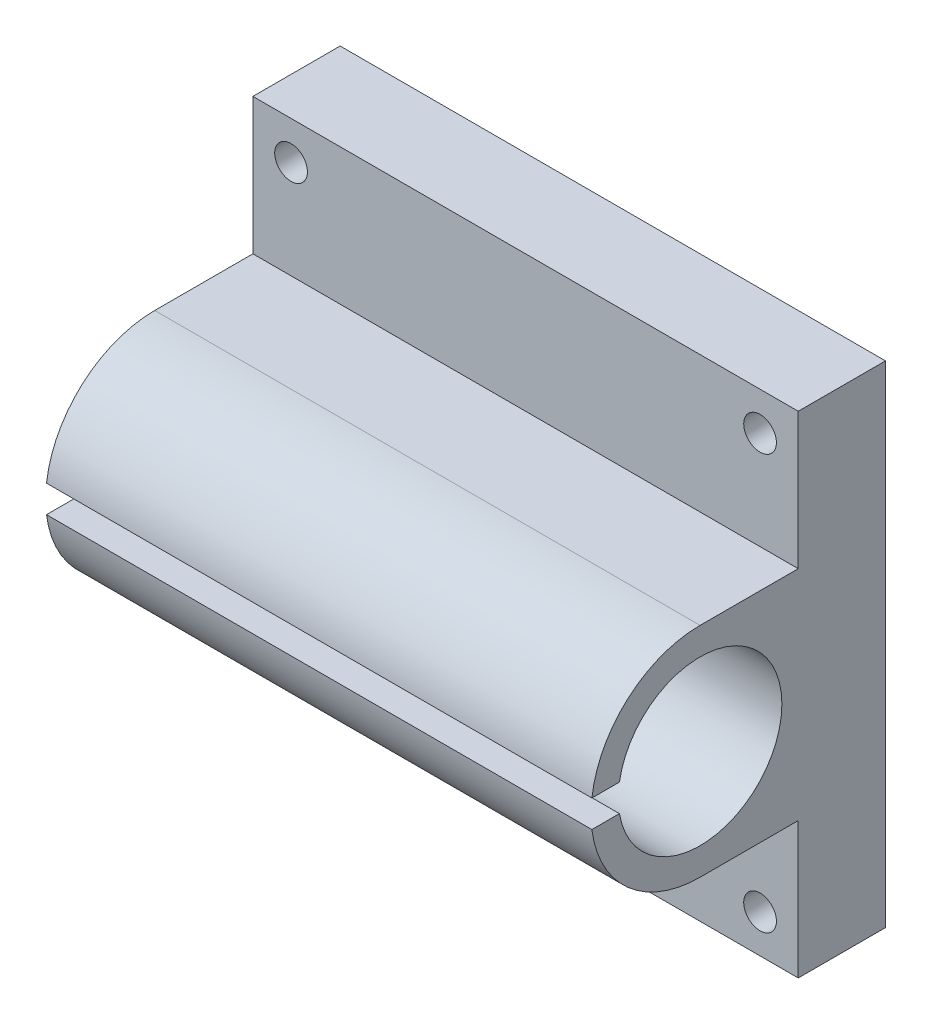
SolidWorks part; units mm, degrees
ref_plane "前视基准面" through (0, 0, 0) normal (0, 0, 1) x (1, 0, 0)
ref_plane "上视基准面" through (0, 0, 0) normal (0, 1, 0) x (1, 0, 0)
ref_plane "右视基准面" through (0, 0, 0) normal (1, 0, 0) x (0, 0, -1)
sketch "草图1" plane through (0, 0, 0) normal (0, 0, 1) x (1, 0, 0)
  line L1 (-25, -22.5) -> (25, -22.5)
  line L2 (-25, -22.5) -> (-25, 22.5)
  line L3 (-25, 22.5) -> (25, 22.5)
  line L4 (25, -22.5) -> (25, 22.5)
  line L5 (-25, -22.5) -> (25, 22.5) construction
  line L6 (-25, 22.5) -> (25, -22.5) construction
  point P0 (0, 0)
  dimension "D1" = 45
  dimension "D2" = 50
extrude "凸台-拉伸1" add sketch "草图1" along normal blind 8
sketch "草图2" plane through (25, 0, 0) normal (1, 0, 0) x (0, 0, -1)
  line L0 (-8, -22.5) -> (-8, 22.5) construction
  line L1 (-8, 10) -> (-17, 10)
  line L2 (-8, 10) -> (-8, -10)
  line L3 (-8, -10) -> (-17, -10)
  line L5 (0, -22.5) -> (0, 22.5) construction
  line L6 (-28, 0) -> (-8, 0) construction
  circle A0 centre (-17, 0) radius 7.5
  arc A1 (-17, 10) -> (-17, -10) centre (-17, 0) ccw
  dimension "D3" = 15
  dimension "D4" = 17
extrude "凸台-拉伸2" add sketch "草图2" against normal up to surface (50 mm away) up to face at (-25, 0, 4)
sketch "草图3" plane through (25, 0, 0) normal (1, 0, 0) x (0, 0, -1)
  line L1 (-27.5, -1.25) -> (-21.5, -1.25)
  line L2 (-27.5, -1.25) -> (-27.5, 1.25)
  line L3 (-27.5, 1.25) -> (-21.5, 1.25)
  line L4 (-21.5, -1.25) -> (-21.5, 1.25)
  line L5 (-27.5, -1.25) -> (-21.5, 1.25) construction
  line L6 (-27.5, 1.25) -> (-21.5, -1.25) construction
  circle A0 centre (-17, 0) radius 7.5 construction
  point P0 (-24.5, 0)
  dimension "D1" = 2.5
  dimension "D2" = 6
extrude "切除-拉伸1" cut sketch "草图3" against normal blind 58
sketch "草图4" plane through (0, 0, 0) normal (0, 0, -1) x (-1, 0, 0)
  line L0 (-25, 0) -> (25, 0) construction
  line L1 (-25, -22.5) -> (-25, 22.5) construction
  line L2 (25, 22.5) -> (25, -22.5) construction
sketch "草图5" plane through (0, 0, 8) normal (0, 0, 1) x (1, 0, 0)
  line L0 (0, 22.5) -> (0, -22.5) construction
  line L1 (25, 22.5) -> (-25, 22.5) construction
  line L2 (-25, -22.5) -> (25, -22.5) construction
  line L3 (-25, 22.5) -> (-25, 10) construction
  line L4 (25, 0) -> (-25, 0) construction
  line L5 (25, 0) -> (-25, 0) construction
  circle A0 centre (-21.5, 19) radius 1.5
  circle A1 centre (21.5, 19) radius 1.5
  circle A2 centre (21.5, -19) radius 1.5
  circle A3 centre (-21.5, -19) radius 1.5
  dimension "D1" = 3
  dimension "D3" = 3.5
  dimension "D2" = 3.5
extrude "切除-拉伸2" cut sketch "草图5" against normal blind 10
